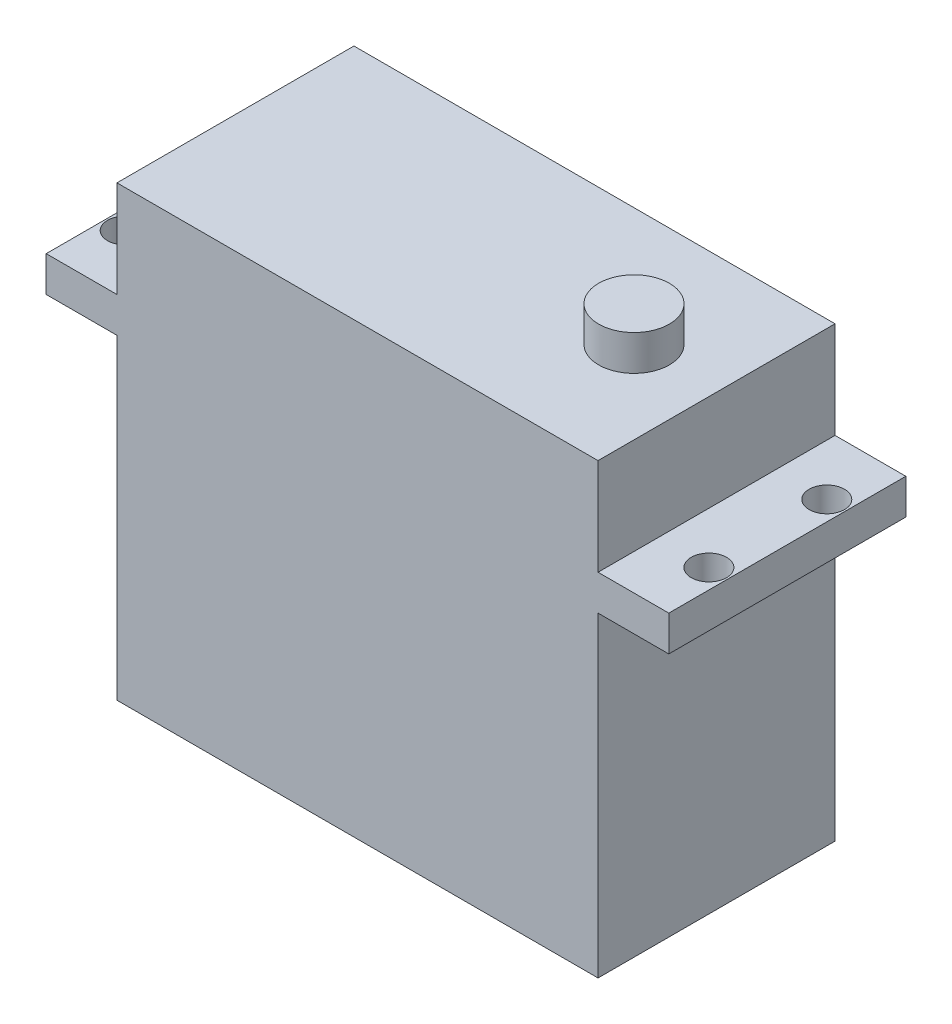
SolidWorks part; units mm, degrees
ref_plane "Front Plane" through (0, 0, 0) normal (0, 0, 1) x (1, 0, 0)
ref_plane "Top Plane" through (0, 0, 0) normal (0, 1, 0) x (1, 0, 0)
ref_plane "Right Plane" through (0, 0, 0) normal (1, 0, 0) x (0, 0, -1)
sketch "Sketch1" plane through (0, 0, 0) normal (0, 0, 1) x (1, 0, 0)
  line L0 (0, 0) -> (40.8, 0)
  line L1 (40.8, 0) -> (40.8, 26.8)
  line L2 (40.8, 26.8) -> (46.8, 26.8)
  line L3 (46.8, 26.8) -> (46.8, 29.8)
  line L4 (46.8, 29.8) -> (40.8, 29.8)
  line L5 (40.8, 29.8) -> (40.8, 38)
  line L6 (40.8, 38) -> (0, 38)
  line L7 (0, 38) -> (0, 29.8)
  line L8 (0, 29.8) -> (-6, 29.8)
  line L9 (-6, 29.8) -> (-6, 26.8)
  line L10 (-6, 26.8) -> (0, 26.8)
  line L11 (0, 26.8) -> (0, 0)
  dimension "D1" = 40.8
  dimension "D2" = 26.8
  dimension "D3" = 3
  dimension "D4" = 6
  dimension "D5" = 38
extrude "Boss-Extrude1" add sketch "Sketch1" along normal blind 20.1
sketch "Sketch2" plane through (0, 38, 0) normal (0, 1, 0) x (1, 0, 0)
  line L3 (40.8, -20.1) -> (40.8, 0) construction
  circle A1 centre (33.8, -10.05) radius 3
  point P2 (40.8, -10.05)
  point P3 (0, 0)
  dimension "D1" = 6
  dimension "D2" = 7
extrude "Boss-Extrude2" add sketch "Sketch2" along normal blind 3
sketch "Sketch3" plane through (0, 29.8, 0) normal (0, 1, 0) x (1, 0, 0)
  line L0 (45.15, -15.05) -> (45.15, -5.05) construction
  line L1 (46.8, -20.1) -> (46.8, 0) construction
  line L2 (20.4, -20.1) -> (20.4, 0) construction
  line L3 (40.8, -20.1) -> (0, -20.1) construction
  line L4 (40.8, 0) -> (0, 0) construction
  line L5 (-4.35, -15.05) -> (-4.35, -5.05) construction
  circle A0 centre (45.15, -15.05) radius 1.5
  circle A1 centre (45.15, -5.05) radius 1.5
  circle A2 centre (-4.35, -5.05) radius 1.5
  circle A3 centre (-4.35, -15.05) radius 1.5
  point P4 (45.15, -10.05)
  point P5 (46.8, -10.05)
  point P18 (-4.35, -10.05)
  dimension "D3" = 3
  dimension "D1" = 10
  dimension "D2" = 49.5
extrude "Cut-Extrude1" cut sketch "Sketch3" against normal up to next
